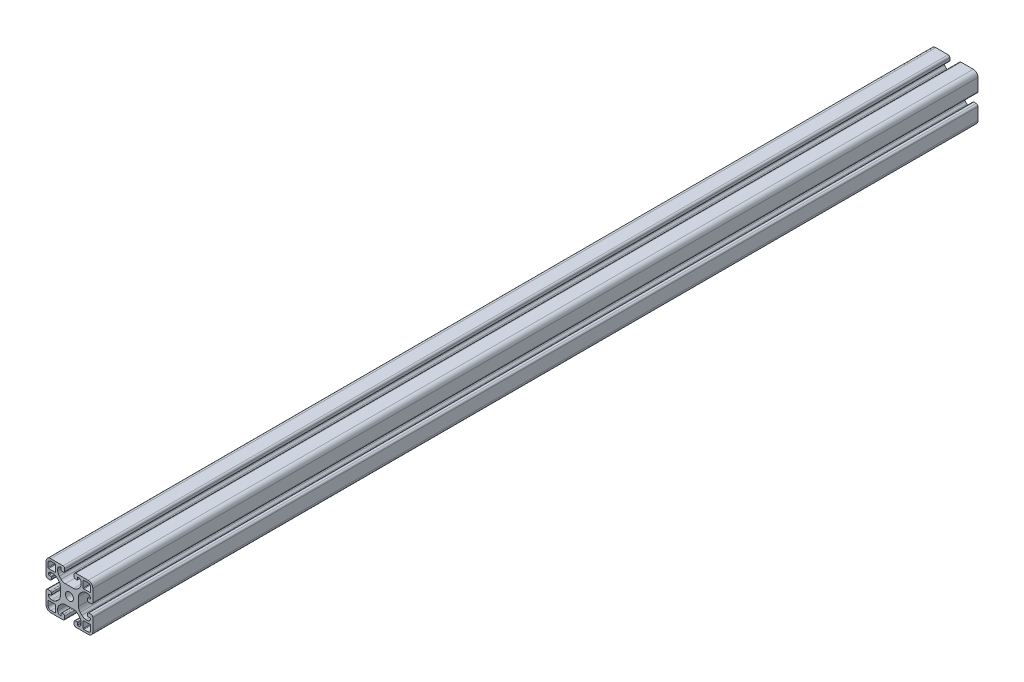
SolidWorks part; units mm, degrees
ref_plane "Plan de face" through (0, 0, 0) normal (0, 0, 1) x (1, 0, 0)
ref_plane "Plan de dessus" through (0, 0, 0) normal (0, 1, 0) x (1, 0, 0)
ref_plane "Plan de droite" through (0, 0, 0) normal (1, 0, 0) x (0, 0, -1)
ref_plane "Plan1" through (0, 0, -30) normal (0, 0, -1) x (-1, 0, 0)
sketch "Esquisse1" plane through (0, 0, -30) normal (0, 0, -1) x (-1, 0, 0)
  line L0 (-4.5, 15) -> (-4.5, 13.5)
  line L1 (-4, 13) -> (-2.5, 13)
  line L2 (-4.5, 10) -> (-5.8076, 10)
  line L3 (-9.3431, 11.4645) -> (-10.7855, 12.9069)
  line L4 (-12.25, 16.4424) -> (-12.25, 23.5576)
  line L5 (-10.7855, 27.0931) -> (-9.3431, 28.5355)
  line L6 (-5.8076, 30) -> (-4.5, 30)
  line L7 (-2.5, 27) -> (-4, 27)
  line L8 (-4.5, 26.5) -> (-4.5, 25)
  line L9 (-3.5, 24) -> (-1.5, 24)
  line L10 (0, 25.5) -> (0, 36)
  line L11 (-4, 40) -> (-14.5, 40)
  line L12 (-16, 38.5) -> (-16, 36.5)
  line L13 (-15, 35.5) -> (-13.5, 35.5)
  line L14 (-13, 36) -> (-13, 37.5)
  line L15 (-10, 35.5) -> (-10, 34.1924)
  line L16 (-11.4645, 30.6569) -> (-12.9069, 29.2145)
  line L17 (-16.4424, 27.75) -> (-23.5576, 27.75)
  line L18 (-27.0931, 29.2145) -> (-28.5355, 30.6569)
  line L19 (-30, 34.1924) -> (-30, 35.5)
  line L20 (-27, 37.5) -> (-27, 36)
  line L21 (-26.5, 35.5) -> (-25, 35.5)
  line L22 (-24, 36.5) -> (-24, 38.5)
  line L23 (-25.5, 40) -> (-36, 40)
  line L24 (-40, 36) -> (-40, 25.5)
  line L25 (-38.5, 24) -> (-36.5, 24)
  line L26 (-35.5, 25) -> (-35.5, 26.5)
  line L27 (-36, 27) -> (-37.5, 27)
  line L28 (-35.5, 30) -> (-34.1924, 30)
  line L29 (-30.6569, 28.5355) -> (-29.2145, 27.0931)
  line L30 (-27.75, 23.5576) -> (-27.75, 16.4424)
  line L31 (-29.2145, 12.9069) -> (-30.6569, 11.4645)
  line L32 (-34.1924, 10) -> (-35.5, 10)
  line L33 (-37.5, 13) -> (-36, 13)
  line L34 (-35.5, 13.5) -> (-35.5, 15)
  line L35 (-36.5, 16) -> (-38.5, 16)
  line L36 (-40, 14.5) -> (-40, 4)
  line L37 (-36, 0) -> (-25.5, 0)
  line L38 (-24, 1.5) -> (-24, 3.5)
  line L39 (-25, 4.5) -> (-26.5, 4.5)
  line L40 (-27, 4) -> (-27, 2.5)
  line L41 (-30, 4.5) -> (-30, 5.8076)
  line L42 (-28.5355, 9.3431) -> (-27.0931, 10.7855)
  line L43 (-23.5576, 12.25) -> (-16.4424, 12.25)
  line L44 (-12.9069, 10.7855) -> (-11.4645, 9.3431)
  line L45 (-10, 5.8076) -> (-10, 4.5)
  line L46 (-13, 2.5) -> (-13, 4)
  line L47 (-13.5, 4.5) -> (-15, 4.5)
  line L48 (-16, 3.5) -> (-16, 1.5)
  line L49 (-14.5, 0) -> (-4, 0)
  line L50 (0, 4) -> (0, 14.5)
  line L51 (-1.5, 16) -> (-3.5, 16)
  line L52 (-4, 1.8) -> (-7.7, 1.8)
  line L53 (-8.2, 2.3) -> (-8.2, 7.7)
  line L54 (-7.7, 8.2) -> (-2.3, 8.2)
  line L55 (-1.8, 7.7) -> (-1.8, 4)
  line L56 (-38.2, 4) -> (-38.2, 7.7)
  line L57 (-37.7, 8.2) -> (-32.3, 8.2)
  line L58 (-31.8, 7.7) -> (-31.8, 2.3)
  line L59 (-32.3, 1.8) -> (-36, 1.8)
  line L60 (-36, 38.2) -> (-32.3, 38.2)
  line L61 (-31.8, 37.7) -> (-31.8, 32.3)
  line L62 (-32.3, 31.8) -> (-37.7, 31.8)
  line L63 (-38.2, 32.3) -> (-38.2, 36)
  line L64 (-1.8, 36) -> (-1.8, 32.3)
  line L65 (-2.3, 31.8) -> (-7.7, 31.8)
  line L66 (-8.2, 32.3) -> (-8.2, 37.7)
  line L67 (-7.7, 38.2) -> (-4, 38.2)
  arc A0 (-4.5, 13.5) -> (-4, 13) centre (-4, 13.5) ccw
  arc A1 (-2.5, 13) -> (-2, 12.5) centre (-2.5, 12.5) cw
  arc A2 (-2, 12.5) -> (-4.5, 10) centre (-4.5, 12.5) cw
  arc A3 (-5.8076, 10) -> (-9.3431, 11.4645) centre (-5.8076, 15) cw
  arc A4 (-10.7855, 12.9069) -> (-12.25, 16.4424) centre (-7.25, 16.4424) cw
  arc A5 (-12.25, 23.5576) -> (-10.7855, 27.0931) centre (-7.25, 23.5576) cw
  arc A6 (-9.3431, 28.5355) -> (-5.8076, 30) centre (-5.8076, 25) cw
  arc A7 (-4.5, 30) -> (-2, 27.5) centre (-4.5, 27.5) cw
  arc A8 (-2, 27.5) -> (-2.5, 27) centre (-2.5, 27.5) cw
  arc A9 (-4, 27) -> (-4.5, 26.5) centre (-4, 26.5) ccw
  arc A10 (-4.5, 25) -> (-3.5, 24) centre (-3.5, 25) ccw
  arc A11 (-1.5, 24) -> (0, 25.5) centre (-1.5, 25.5) ccw
  arc A12 (0, 36) -> (-4, 40) centre (-4, 36) ccw
  arc A13 (-14.5, 40) -> (-16, 38.5) centre (-14.5, 38.5) ccw
  arc A14 (-16, 36.5) -> (-15, 35.5) centre (-15, 36.5) ccw
  arc A15 (-13.5, 35.5) -> (-13, 36) centre (-13.5, 36) ccw
  arc A16 (-13, 37.5) -> (-12.5, 38) centre (-12.5, 37.5) cw
  arc A17 (-12.5, 38) -> (-10, 35.5) centre (-12.5, 35.5) cw
  arc A18 (-10, 34.1924) -> (-11.4645, 30.6569) centre (-15, 34.1924) cw
  arc A19 (-12.9069, 29.2145) -> (-16.4424, 27.75) centre (-16.4424, 32.75) cw
  arc A20 (-23.5576, 27.75) -> (-27.0931, 29.2145) centre (-23.5576, 32.75) cw
  arc A21 (-28.5355, 30.6569) -> (-30, 34.1924) centre (-25, 34.1924) cw
  arc A22 (-30, 35.5) -> (-27.5, 38) centre (-27.5, 35.5) cw
  arc A23 (-27.5, 38) -> (-27, 37.5) centre (-27.5, 37.5) cw
  arc A24 (-27, 36) -> (-26.5, 35.5) centre (-26.5, 36) ccw
  arc A25 (-25, 35.5) -> (-24, 36.5) centre (-25, 36.5) ccw
  arc A26 (-24, 38.5) -> (-25.5, 40) centre (-25.5, 38.5) ccw
  arc A27 (-36, 40) -> (-40, 36) centre (-36, 36) ccw
  arc A28 (-40, 25.5) -> (-38.5, 24) centre (-38.5, 25.5) ccw
  arc A29 (-36.5, 24) -> (-35.5, 25) centre (-36.5, 25) ccw
  arc A30 (-35.5, 26.5) -> (-36, 27) centre (-36, 26.5) ccw
  arc A31 (-37.5, 27) -> (-38, 27.5) centre (-37.5, 27.5) cw
  arc A32 (-38, 27.5) -> (-35.5, 30) centre (-35.5, 27.5) cw
  arc A33 (-34.1924, 30) -> (-30.6569, 28.5355) centre (-34.1924, 25) cw
  arc A34 (-29.2145, 27.0931) -> (-27.75, 23.5576) centre (-32.75, 23.5576) cw
  arc A35 (-27.75, 16.4424) -> (-29.2145, 12.9069) centre (-32.75, 16.4424) cw
  arc A36 (-30.6569, 11.4645) -> (-34.1924, 10) centre (-34.1924, 15) cw
  arc A37 (-35.5, 10) -> (-38, 12.5) centre (-35.5, 12.5) cw
  arc A38 (-38, 12.5) -> (-37.5, 13) centre (-37.5, 12.5) cw
  arc A39 (-36, 13) -> (-35.5, 13.5) centre (-36, 13.5) ccw
  arc A40 (-35.5, 15) -> (-36.5, 16) centre (-36.5, 15) ccw
  arc A41 (-38.5, 16) -> (-40, 14.5) centre (-38.5, 14.5) ccw
  arc A42 (-40, 4) -> (-36, 0) centre (-36, 4) ccw
  arc A43 (-25.5, 0) -> (-24, 1.5) centre (-25.5, 1.5) ccw
  arc A44 (-24, 3.5) -> (-25, 4.5) centre (-25, 3.5) ccw
  arc A45 (-26.5, 4.5) -> (-27, 4) centre (-26.5, 4) ccw
  arc A46 (-27, 2.5) -> (-27.5, 2) centre (-27.5, 2.5) cw
  arc A47 (-27.5, 2) -> (-30, 4.5) centre (-27.5, 4.5) cw
  arc A48 (-30, 5.8076) -> (-28.5355, 9.3431) centre (-25, 5.8076) cw
  arc A49 (-27.0931, 10.7855) -> (-23.5576, 12.25) centre (-23.5576, 7.25) cw
  arc A50 (-16.4424, 12.25) -> (-12.9069, 10.7855) centre (-16.4424, 7.25) cw
  arc A51 (-11.4645, 9.3431) -> (-10, 5.8076) centre (-15, 5.8076) cw
  arc A52 (-10, 4.5) -> (-12.5, 2) centre (-12.5, 4.5) cw
  arc A53 (-12.5, 2) -> (-13, 2.5) centre (-12.5, 2.5) cw
  arc A54 (-13, 4) -> (-13.5, 4.5) centre (-13.5, 4) ccw
  arc A55 (-15, 4.5) -> (-16, 3.5) centre (-15, 3.5) ccw
  arc A56 (-16, 1.5) -> (-14.5, 0) centre (-14.5, 1.5) ccw
  arc A57 (-4, 0) -> (0, 4) centre (-4, 4) ccw
  arc A58 (0, 14.5) -> (-1.5, 16) centre (-1.5, 14.5) ccw
  arc A59 (-3.5, 16) -> (-4.5, 15) centre (-3.5, 15) ccw
  circle A60 centre (-20, 20) radius 3.4
  arc A61 (-1.8, 4) -> (-4, 1.8) centre (-4, 4) cw
  arc A62 (-7.7, 1.8) -> (-8.2, 2.3) centre (-7.7, 2.3) cw
  arc A63 (-8.2, 7.7) -> (-7.7, 8.2) centre (-7.7, 7.7) cw
  arc A64 (-2.3, 8.2) -> (-1.8, 7.7) centre (-2.3, 7.7) cw
  arc A65 (-36, 1.8) -> (-38.2, 4) centre (-36, 4) cw
  arc A66 (-38.2, 7.7) -> (-37.7, 8.2) centre (-37.7, 7.7) cw
  arc A67 (-32.3, 8.2) -> (-31.8, 7.7) centre (-32.3, 7.7) cw
  arc A68 (-31.8, 2.3) -> (-32.3, 1.8) centre (-32.3, 2.3) cw
  arc A69 (-38.2, 36) -> (-36, 38.2) centre (-36, 36) cw
  arc A70 (-32.3, 38.2) -> (-31.8, 37.7) centre (-32.3, 37.7) cw
  arc A71 (-31.8, 32.3) -> (-32.3, 31.8) centre (-32.3, 32.3) cw
  arc A72 (-37.7, 31.8) -> (-38.2, 32.3) centre (-37.7, 32.3) cw
  arc A73 (-4, 38.2) -> (-1.8, 36) centre (-4, 36) cw
  arc A74 (-1.8, 32.3) -> (-2.3, 31.8) centre (-2.3, 32.3) cw
  arc A75 (-7.7, 31.8) -> (-8.2, 32.3) centre (-7.7, 32.3) cw
  arc A76 (-8.2, 37.7) -> (-7.7, 38.2) centre (-7.7, 37.7) cw
extrude "Boss.-Extru.1" add sketch "Esquisse1" against normal blind 756
